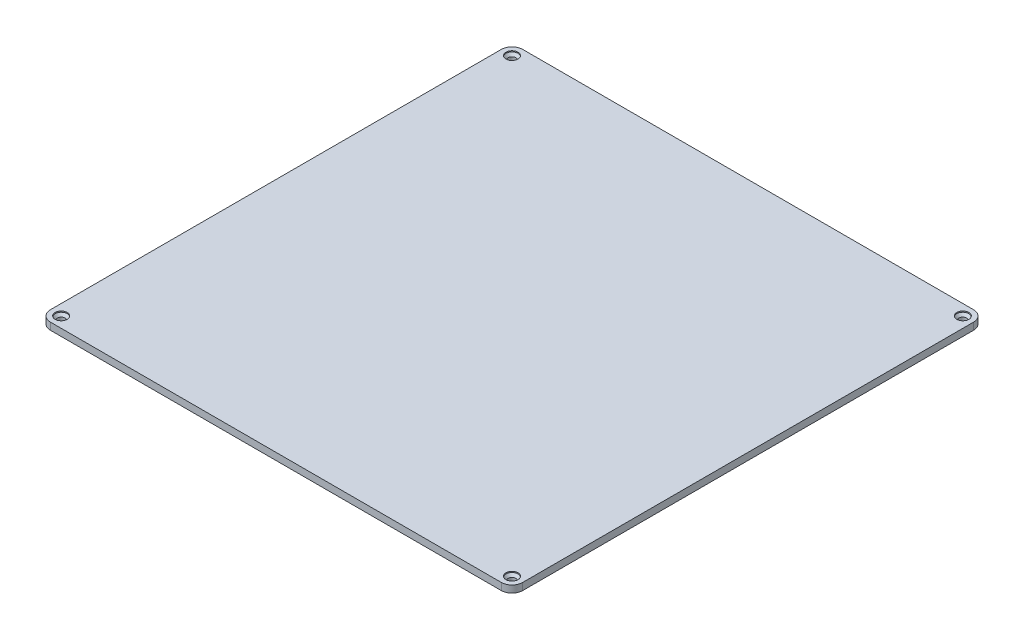
SolidWorks part; units mm, degrees
ref_plane "Front Plane" through (0, 0, 0) normal (0, 0, 1) x (1, 0, 0)
ref_plane "Top Plane" through (0, 0, 0) normal (0, 1, 0) x (1, 0, 0)
ref_plane "Right Plane" through (0, 0, 0) normal (1, 0, 0) x (0, 0, -1)
sketch "Sketch1" plane through (0, 0, 0) normal (0, 1, 0) x (1, 0, 0)
  line L1 (-110, 110) -> (110, 110)
  line L2 (-110, 110) -> (-110, -110)
  line L3 (-110, -110) -> (110, -110)
  line L4 (110, 110) -> (110, -110)
  dimension "D1" = 220
  dimension "D2" = 220
  dimension "D3" = 110
  dimension "D4" = 110
extrude "Extrude1" add sketch "Sketch1" along normal blind 3.3
fillet "Fillet1" radius 5 4 edges at (-110, 1.65, -110) (-110, 1.65, 110) (110, 1.65, -110) (110, 1.65, 110)
sketch "Sketch2" plane through (0, 3.3, 0) normal (0, 1, 0) x (1, 0, 0)
  line L0 (105, 110) -> (-105, 110) construction
  line L1 (-105, 105) -> (105, 105)
  line L2 (-105, 105) -> (-105, -105)
  line L3 (-105, -105) -> (105, -105)
  line L4 (105, 105) -> (105, -105)
  line L5 (-110, 105) -> (-110, -105) construction
  circle A0 centre (-105, 105) radius 1.75
  circle A1 centre (105, 105) radius 1.75
  circle A2 centre (-105, -105) radius 1.75
  circle A3 centre (105, -105) radius 1.75
  dimension "D5" = 3.5
  dimension "D1" = 210
  dimension "D2" = 210
  dimension "D3" = 5
  dimension "D4" = 5
extrude "Extrude2" cut sketch "Sketch2" against normal blind 3.3 contours A0 | A1 | A3 | A2
ref_plane "Plane1" through (0, 0, -105) normal (0, 0, -1) x (-1, 0, 0)
sketch "Sketch3" plane through (0, 0, -105) normal (0, 0, -1) x (-1, 0, 0)
  line L0 (110, 3.3) -> (105, 3.3) construction
  line L2 (110, 3.3) -> (105, 3.3) construction
  line L4 (105, 3.3) -> (107.8, 3.3)
  line L5 (107.8, 3.3) -> (107.8, 2.8)
  line L6 (107.8, 2.8) -> (106.5, 1.3)
  line L7 (106.5, 1.3) -> (105, 1.3)
  line L8 (105, 0) -> (105, 3.3) construction
  line L9 (105, 1.3) -> (105, 3.3)
  dimension "D1" = 5
  dimension "D2" = 2
  dimension "D3" = 1.5
  dimension "D4" = 1.5
  dimension "D5" = 2.8
revolve "Cut-Revolve1" cut sketch "Sketch3" angle 360 about L9
pattern_linear "LPattern1" count 2 spacing 210 along (1, 0, 0) count 2 spacing 210 along (0, 0, 1) of "Cut-Revolve1"
